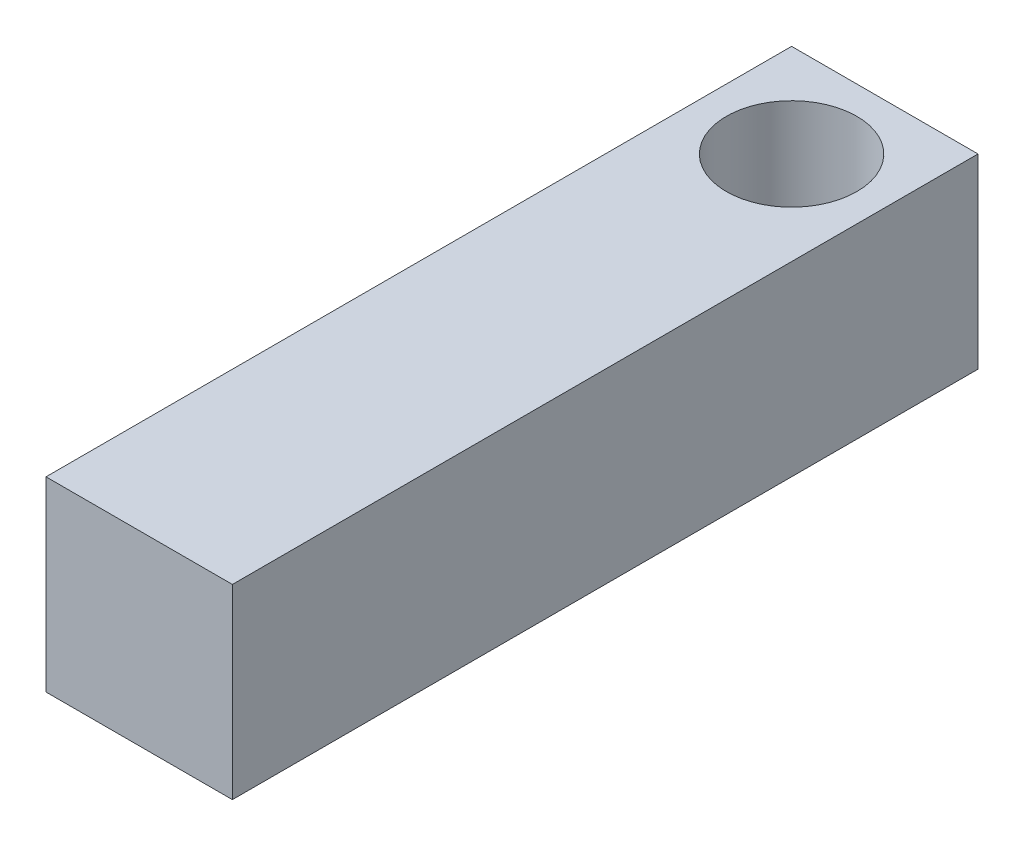
SolidWorks part; units mm, degrees
ref_plane "Piano frontale" through (0, 0, 0) normal (0, 0, 1) x (1, 0, 0)
ref_plane "Piano superiore" through (0, 0, 0) normal (0, 1, 0) x (1, 0, 0)
ref_plane "Piano destro" through (0, 0, 0) normal (1, 0, 0) x (0, 0, -1)
sketch "Schizzo1" plane through (0, 0, 0) normal (0, 0, 1) x (1, 0, 0)
  line L0 (0, 0) -> (-5, 0)
  line L1 (-5, 0) -> (-5, 5)
  line L2 (-5, 5) -> (0, 5)
  line L3 (0, 5) -> (0, 0)
  dimension "D1" = 5
extrude "Estrusione-Estrusione1" add sketch "Schizzo1" along normal blind 20
sketch "Schizzo2" plane through (0, 0, 0) normal (0, -1, 0) x (-1, 0, 0)
  line L0 (5, 0) -> (0, 0) construction
  line L1 (2.5, -20) -> (2.5, 3.3709) construction
  line L2 (5, -20) -> (0, -20) construction
  circle A0 centre (2.5, -27.5) radius 1.75
  circle A1 centre (2.5, -2.5) radius 1.75
  dimension "D3" = 3.5
  dimension "D1" = 25
  dimension "D2" = 2.5
extrude "Taglio-Estrusione1" cut sketch "Schizzo2" against normal through all
